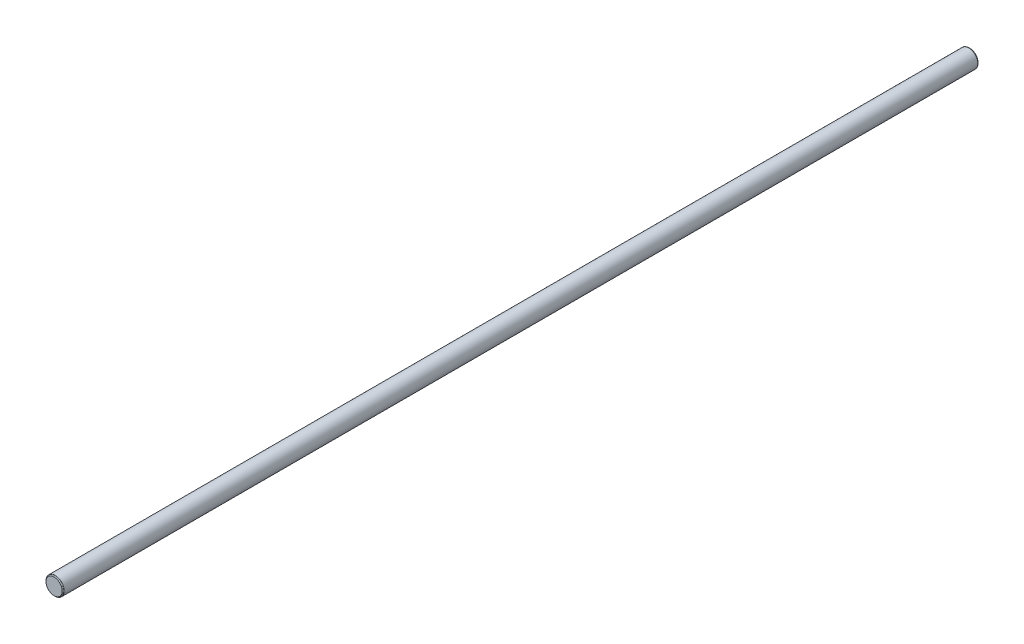
SolidWorks part; units mm, degrees
ref_plane "Front Plane" through (0, 0, 0) normal (0, 0, 1) x (1, 0, 0)
ref_plane "Top Plane" through (0, 0, 0) normal (0, 1, 0) x (1, 0, 0)
ref_plane "Right Plane" through (0, 0, 0) normal (1, 0, 0) x (0, 0, -1)
sketch "Sketch1" plane through (0, 0, 0) normal (0, 0, 1) x (1, 0, 0)
  line L0 (-3, 0) -> (3, 0) construction
  point P4 (0, 0)
  dimension "Diameter" = 6
sketch "Sketch2" plane through (0, 0, 0) normal (1, 0, 0) x (0, 0, -1)
  line L0 (152.4, 0) -> (-152.4, 0) construction
  point P0 (-143.4, 0)
  point P4 (0, 0)
  point P6 (143.4, 0)
  dimension "Length" = 304.8
  dimension "D1" = 9
  dimension "D2" = 9
sketch "Sketch3" plane through (0, 0, 0) normal (0, 0, 1) x (1, 0, 0)
  circle A0 centre (0, 0) radius 3
extrude "Boss-Extrude1" add sketch "Sketch3" along normal mid plane 304.8
chamfer "Chamfer1" distance 0.3 angle 45 2 edges at (3, 0, -152.4) (3, 0, 152.4)
fillet "Fillet1" radius 0.225 2 edges at (3, 0, -152.1) (3, 0, 152.1)
equation "\"D1@Boss-Extrude1\"=\"Length@Sketch2\""
equation "\"D1@Chamfer1\"=\"Diameter@Sketch1\"*.05"
equation "\"D1@Fillet1\"=\"D1@Chamfer1\"*.75"
equation "\"D1@Sketch2\" = \"Diameter@Sketch1\" * 1.5"
equation "\"D2@Sketch2\"=\"D1@Sketch2\""
